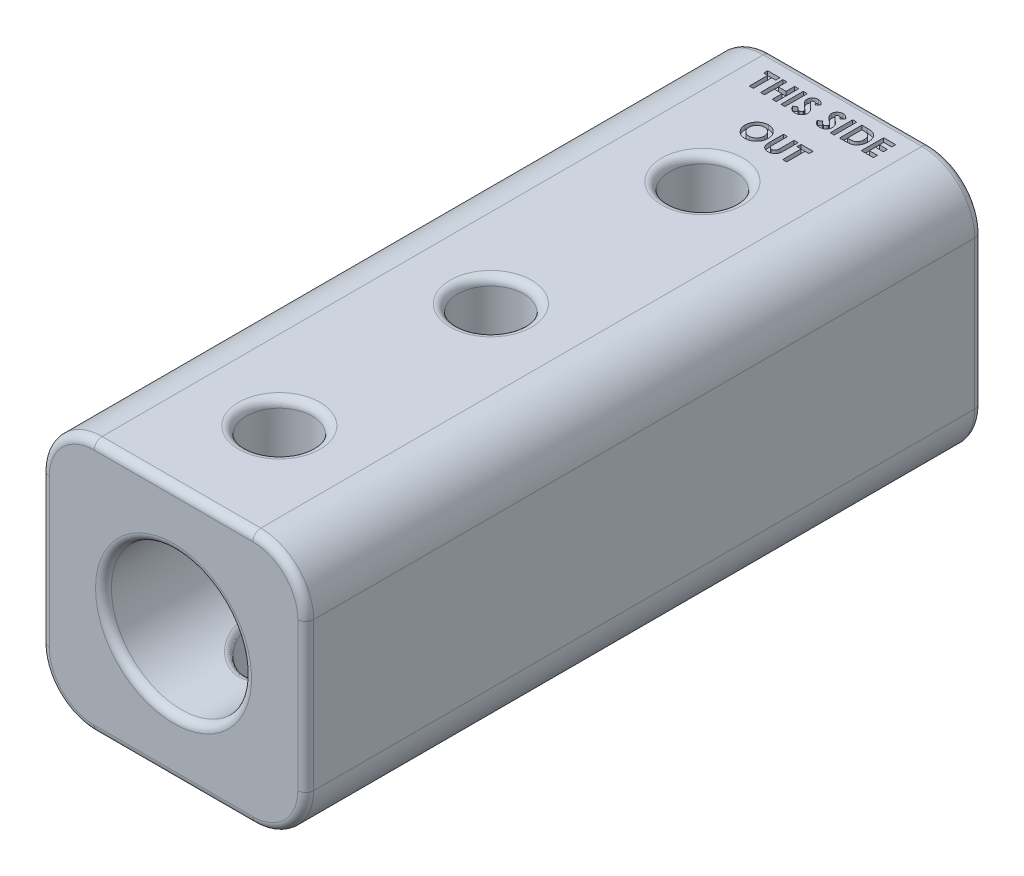
SolidWorks part; units mm, degrees
ref_plane "Front Plane" through (0, 0, 0) normal (0, 0, 1) x (1, 0, 0)
ref_plane "Top Plane" through (0, 0, 0) normal (0, 1, 0) x (1, 0, 0)
ref_plane "Right Plane" through (0, 0, 0) normal (1, 0, 0) x (0, 0, -1)
sketch "Sketch1" plane through (0, 0, 0) normal (0, 0, 1) x (1, 0, 0)
  line L1 (-12.5, -12) -> (12.5, -12)
  line L2 (-12.5, -12) -> (-12.5, 12)
  line L3 (-12.5, 12) -> (12.5, 12)
  line L4 (12.5, -12) -> (12.5, 12)
  line L5 (-12.5, -12) -> (12.5, 12) construction
  line L6 (-12.5, 12) -> (12.5, -12) construction
  circle A0 centre (0, 0) radius 6.625
  point P0 (0, 0)
  dimension "D3" = 13.25
  dimension "D1" = 25
  dimension "D2" = 24
extrude "Boss-Extrude1" add sketch "Sketch1" along normal mid plane 64
sketch "Sketch2" plane through (0, 12, 0) normal (0, 1, 0) x (1, 0, 0)
  line L0 (12.5, -32) -> (-12.5, -32) construction
  circle A0 centre (0, -22) radius 3.1
  circle A1 centre (0, -2) radius 3.1
  circle A2 centre (0, 18) radius 3.1
extrude "Cut-Extrude1" cut sketch "Sketch2" against normal through all
fillet "Fillet1" radius 5 4 edges at (12.5, -12, 0) (-12.5, -12, 0) (-12.5, 12, 0) (12.5, 12, 0)
fillet "Fillet2" radius 0.75 30 edges at (-0.3592, -6.6153, 18.9209) (0.3592, 6.6153, 18.9209) (0, -12, 25.1) (-0.3592, -6.6153, -1.0791) (0.3592, 6.6153, -1.0791) (0, -12, 5.1) (-0.3592, -6.6153, -21.0791) (0.3592, 6.6153, -21.0791) (0, -12, -14.9) (0, 12, 25.1) (0, 12, 5.1) (0, 12, -14.9) (6.625, 0, -32) (6.625, 0, 32) (11.0355, -10.5355, 32) (0, -12, 32) (-11.0355, -10.5355, 32) (-12.5, 0, 32) (-11.0355, 10.5355, 32) (0, 12, 32) (11.0355, 10.5355, 32) (0, 12, -32) (-11.0355, 10.5355, -32) (-12.5, 0, -32) (-11.0355, -10.5355, -32) (0, -12, -32) (11.0355, -10.5355, -32) (12.5, 0, -32) (12.5, 0, 32) (11.0355, 10.5355, -32)
sketch "Sketch3" plane through (0, 12, 0) normal (0, 1, 0) x (1, 0, 0)
  text T0 "<b>THIS SIDE</b>\r\n<b>    OUT</b>" font "Century Gothic" height in points 8
extrude "Cut-Extrude2" cut sketch "Sketch3" against normal blind 0.4
equation "\"D4@Sketch2\"=\"D3@Sketch2\""
